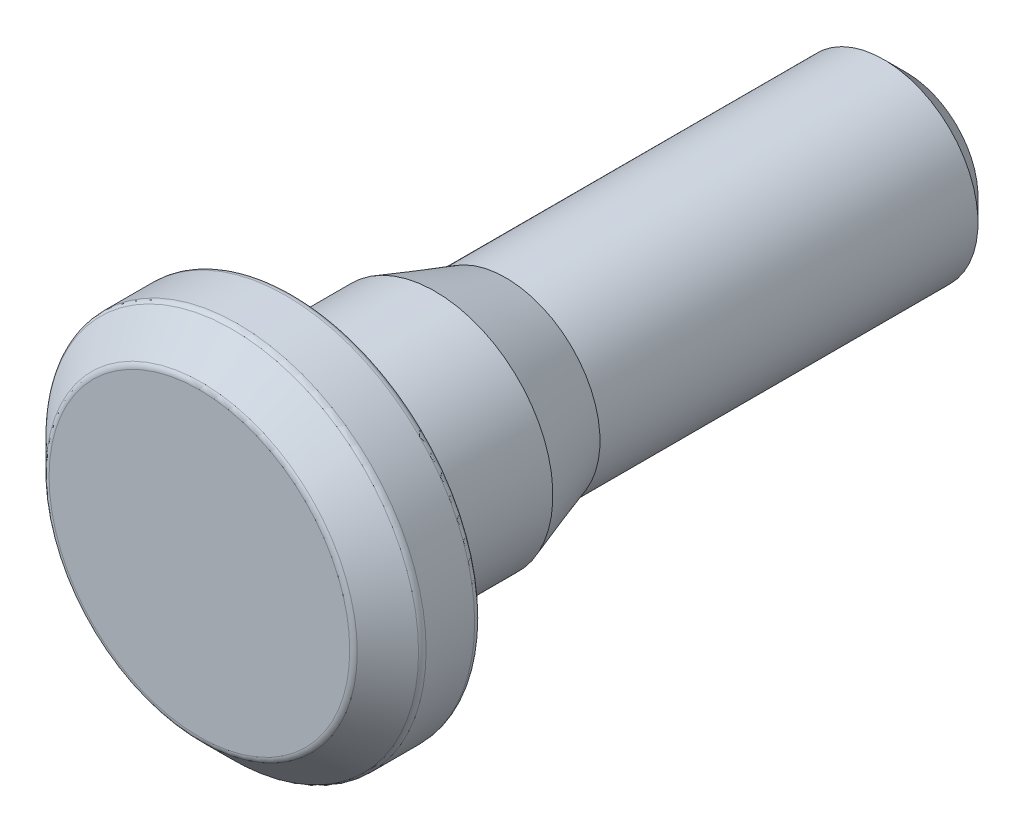
SolidWorks part; units mm, degrees
ref_plane "front" through (0, 0, 0) normal (0, 0, 1) x (1, 0, 0)
ref_plane "top" through (0, 0, 0) normal (0, 1, 0) x (1, 0, 0)
ref_plane "right" through (0, 0, 0) normal (1, 0, 0) x (0, 0, -1)
sketch "Sketch1" plane through (0, 0, 0) normal (1, 0, 0) x (0, 0, -1)
  line L0 (0, 0) -> (-31.5735, 0) construction
  line L1 (-6.35, 0) -> (41.275, 0)
  line L2 (41.275, 0) -> (41.275, 4.826)
  line L3 (41.275, 4.826) -> (39.751, 6.35)
  line L4 (39.751, 6.35) -> (14.2875, 6.35)
  line L5 (14.2875, 6.35) -> (9.525, 7.9375)
  line L6 (9.525, 7.9375) -> (0, 7.9375)
  line L7 (0, 7.9375) -> (0, 12.7)
  line L8 (0, 12.7) -> (-3.9878, 12.7)
  line L9 (-3.9878, 12.7) -> (-6.35, 10.3378)
  line L10 (-6.35, 10.3378) -> (-6.35, 0)
  dimension "D1" = 15.875
  dimension "D2" = 12.7
  dimension "D3" = 25.4
  dimension "D4" = 6.35
  dimension "D5" = 2.3622
  dimension "D6" = 41.275
  dimension "D7" = 9.525
  dimension "D8" = 14.2875
  dimension "D9" = 45
  dimension "D10" = 45
  dimension "D11" = 1.524
revolve "Base-Revolve" add sketch "Sketch1" angle 360 about L0
fillet "Fillet1" radius 0.508
